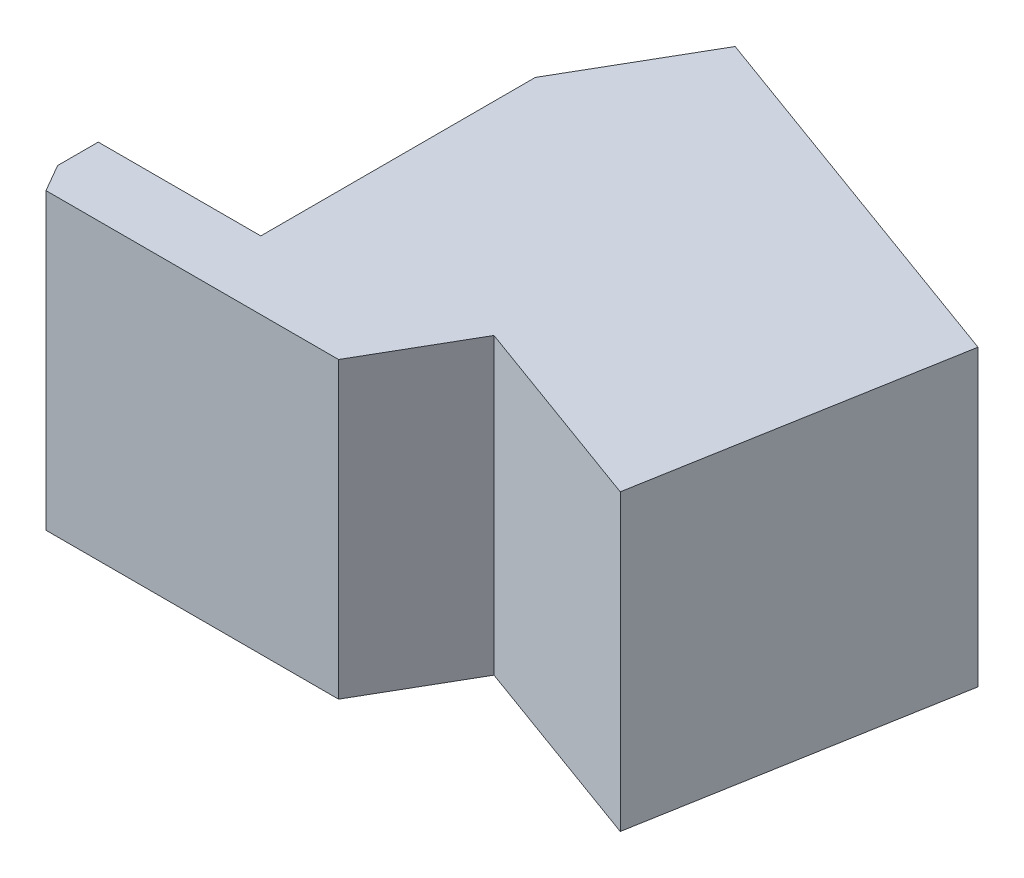
SolidWorks part; units mm, degrees
ref_plane "Front Plane" through (0, 0, 0) normal (0, 0, 1) x (1, 0, 0)
ref_plane "Top Plane" through (0, 0, 0) normal (0, 1, 0) x (1, 0, 0)
ref_plane "Right Plane" through (0, 0, 0) normal (1, 0, 0) x (0, 0, -1)
sketch "Sketch1" plane through (0, 0, 0) normal (0, 1, 0) x (1, 0, 0)
  line L0 (-75, 0) -> (75, 0) construction
  line L1 (0, 75) -> (0, -75) construction
  line L2 (-185, -45) -> (-175.23, -61.9221)
  line L3 (-175.23, -61.9221) -> (4.77, -61.9221)
  line L4 (4.77, -61.9221) -> (39.77, -1.3003)
  line L5 (39.77, -1.3003) -> (161.93, -45.7629)
  line L6 (161.93, -45.7629) -> (194.9232, 141.3506)
  line L7 (194.9232, 141.3506) -> (-40, 226.8556)
  line L8 (-40, 226.8556) -> (-85, 148.9133)
  line L9 (-85, 148.9133) -> (-85, -20)
  line L10 (-85, -20) -> (-185, -20)
  line L11 (-185, -20) -> (-185, -45)
  point P4 (0, 0)
  point P6 (0, 0)
  point P12 (0, 0)
  dimension "D1" = 100
  dimension "D2" = 100
  dimension "D3" = 150
  dimension "D4" = 120
  dimension "D5" = 80
  dimension "D6" = 90
  dimension "D7" = 130
  dimension "D8" = 250
  dimension "D9" = 20
  dimension "D10" = 40
  dimension "D11" = 90
  dimension "D12" = 180
  dimension "D13" = 120
  dimension "D14" = 190
  dimension "D15" = 70
  dimension "D16" = 25
  dimension "D17" = 100
extrude "Boss-Extrude1" add sketch "Sketch1" along normal mid plane 181
